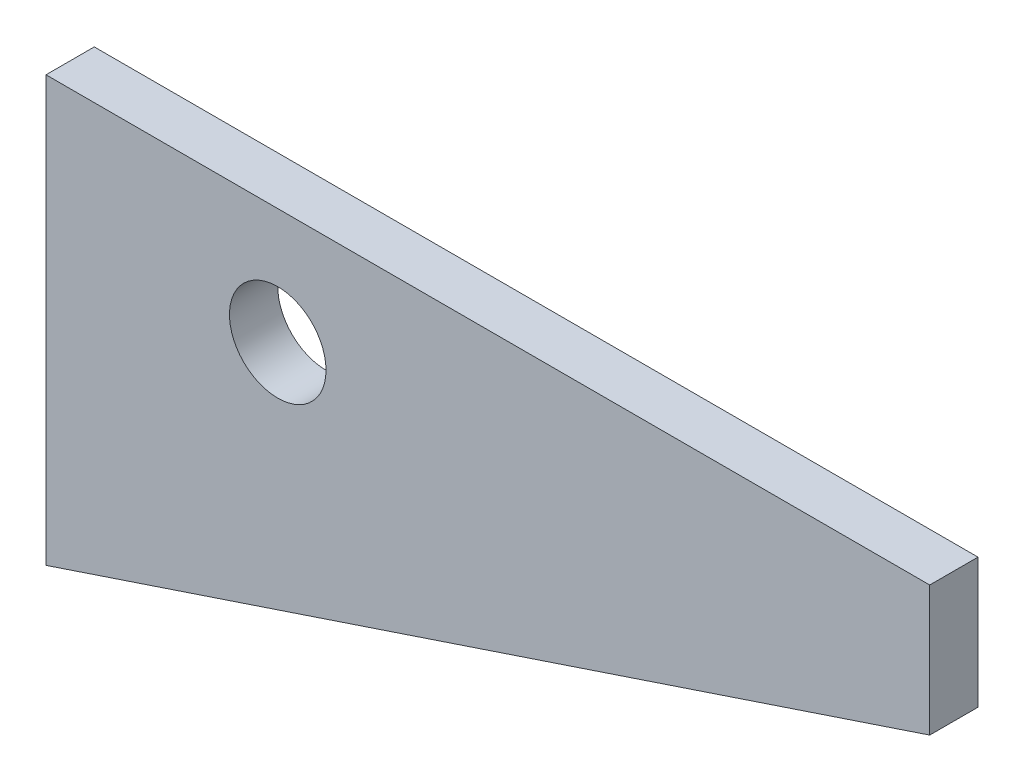
SolidWorks part; units mm, degrees
ref_plane "Front Plane" through (0, 0, 0) normal (0, 0, 1) x (1, 0, 0)
ref_plane "Top Plane" through (0, 0, 0) normal (0, 1, 0) x (1, 0, 0)
ref_plane "Right Plane" through (0, 0, 0) normal (1, 0, 0) x (0, 0, -1)
sketch "Sketch1" plane through (0, 0, 0) normal (0, 0, 1) x (1, 0, 0)
  line L0 (0, 0) -> (145.288, 0)
  line L1 (145.288, 0) -> (145.288, -21.3732)
  line L2 (145.288, -21.3732) -> (0, -69.85)
  line L3 (0, -69.85) -> (0, 0)
  circle A0 centre (38.1, -19.05) radius 7.9375
  dimension "D4" = 15.875
  dimension "D1" = 145.288
  dimension "D2" = 153.162
  dimension "D3" = 69.85
  dimension "D5" = 38.1
  dimension "D6" = 19.05
extrude "Boss-Extrude1" add sketch "Sketch1" along normal blind 7.9375
